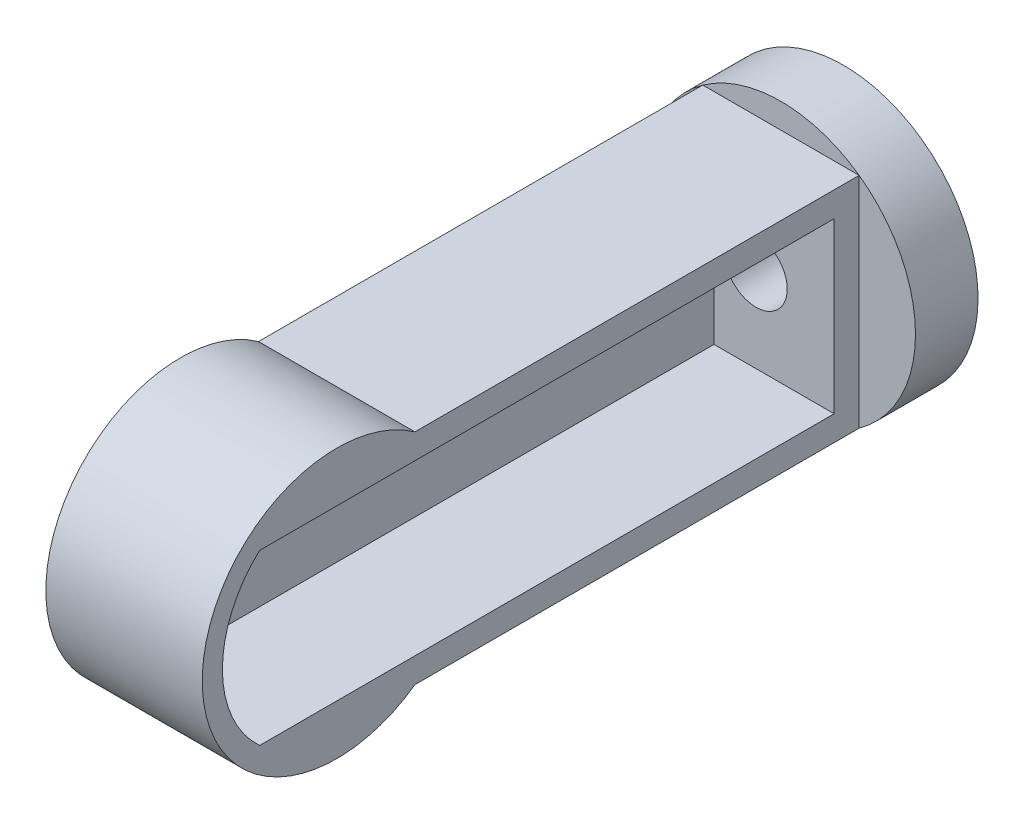
SolidWorks part; units mm, degrees
ref_plane "Alzado" through (0, 0, 0) normal (0, 0, 1) x (1, 0, 0)
ref_plane "Planta" through (0, 0, 0) normal (0, 1, 0) x (1, 0, 0)
ref_plane "Vista lateral" through (0, 0, 0) normal (1, 0, 0) x (0, 0, -1)
sketch "Croquis2" plane through (0, 0, 0) normal (1, 0, 0) x (0, 0, -1)
  line L0 (-45.5622, 0) -> (59.4378, 0) construction
  line L1 (59.4378, 0) -> (59.4378, 17.5) construction
  line L2 (59.4378, 17.5) -> (-11.5722, 17.5) construction
  line L3 (59.4378, 0) -> (59.4378, -17.5) construction
  line L5 (-11.5722, 17.5) -> (59.4378, 17.5)
  line L6 (-11.5722, 17.5) -> (-11.5722, -17.5)
  line L7 (-11.5722, -17.5) -> (59.4378, -17.5)
  line L8 (59.4378, 17.5) -> (59.4378, -17.5)
  circle A0 centre (-24.0622, 0) radius 21.5
  circle A1 centre (-24.0622, 0) radius 5
  dimension "D1" = 105
  dimension "D2" = 43
  dimension "D3" = 17.5
extrude "Saliente-Extruir1" add sketch "Croquis2" along normal mid plane 25 contours L6 A0 | L6 A0 | A0 L7 L8 L5
sketch "Croquis3" plane through (12.5, 0, 0) normal (1, 0, 0) x (0, 0, -1)
  line L5 (55.4378, 13.5) -> (-36.3845, 13.5)
  line L8 (55.4378, 13.5) -> (55.4378, -13.5)
  line L11 (55.4378, -13.5) -> (-36.3845, -13.5)
  line L12 (-36.3845, 13.5) -> (-36.3845, -13.5)
  circle A0 centre (-24.0622, 0) radius 18.2782
  arc A1 (-11.5722, 17.5) -> (-11.5722, -17.5) centre (-24.0622, 0) ccw construction
  point P0 (0, 0)
  dimension "D1" = 3.2218
extrude "Cortar-Extruir1" cut sketch "Croquis3" against normal blind 19.2 contours A0 L11 L8 L5 | L11 A0 L5 L12 | L12 A0
sketch "Croquis4" plane through (0, 0, -59.4378) normal (0, 0, -1) x (-1, 0, 0)
  circle A0 centre (0, 0) radius 21.5
extrude "Saliente-Extruir2" add sketch "Croquis4" along normal blind 10
sketch "Croquis5" plane through (0, 0, -69.4378) normal (0, 0, -1) x (-1, 0, 0)
  circle A0 centre (0, 0) radius 5
extrude "Cortar-Extruir3" cut sketch "Croquis5" against normal blind 19
